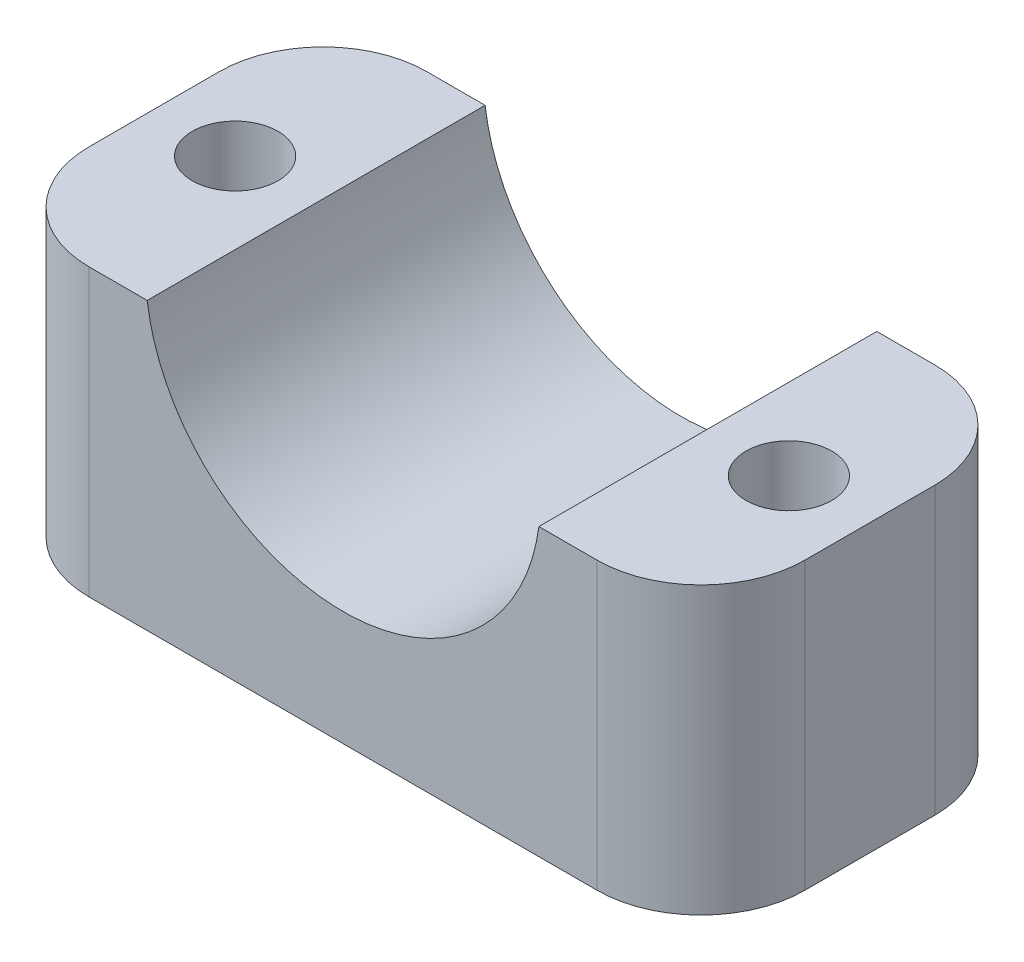
SolidWorks part; units mm, degrees
ref_plane "Front Plane" through (0, 0, 0) normal (0, 0, 1) x (1, 0, 0)
ref_plane "Top Plane" through (0, 0, 0) normal (0, 1, 0) x (1, 0, 0)
ref_plane "Right Plane" through (0, 0, 0) normal (1, 0, 0) x (0, 0, -1)
sketch "Sketch1" plane through (0, 0, 0) normal (0, 0, 1) x (1, 0, 0)
  line L0 (0, 6.5) -> (0, 0) construction
  line L1 (-13.77, -5.5) -> (13.77, -5.5)
  line L2 (-13.77, -5.5) -> (-13.77, 5.5)
  line L3 (-13.77, 5.5) -> (13.77, 5.5)
  line L4 (13.77, -5.5) -> (13.77, 5.5)
  line L5 (-13.77, -5.5) -> (13.77, 5.5) construction
  line L6 (-13.77, 5.5) -> (13.77, -5.5) construction
  circle A0 centre (0, 6.5) radius 7.6
  point P0 (0, 0)
  dimension "D3" = 15.2
  dimension "D1" = 12
  dimension "D2" = 1
  dimension "D4" = 27.54
extrude "Boss-Extrude1" add sketch "Sketch1" along normal blind 13 contours A0 L3 L2 L1 L4
sketch "Sketch2" plane through (0, 5.5, 0) normal (0, 1, 0) x (1, 0, 0)
  line L0 (13.77, 0) -> (7.5339, -13) construction
  line L1 (-13.77, 0) -> (-7.5339, -13) construction
  circle A0 centre (-10.652, -6.5) radius 1.65
  circle A1 centre (10.652, -6.5) radius 1.65
  dimension "D1" = 3.3
extrude "Cut-Extrude1" cut sketch "Sketch2" against normal through all
fillet "Fillet2" radius 4 4 edges at (-13.77, 0, 13) (13.77, 0, 13) (13.77, 0, 0) (-13.77, 0, 0)
